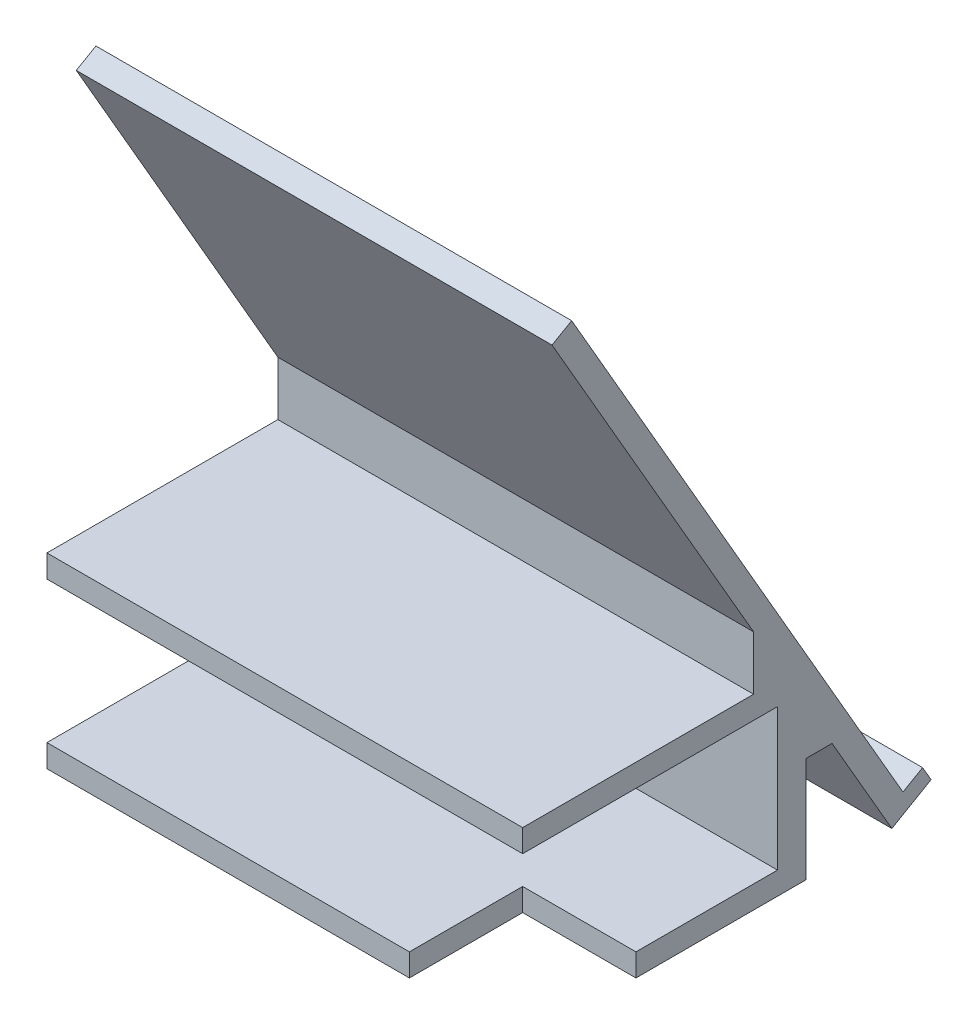
SolidWorks part; units mm, degrees
ref_plane "Спереди" through (0, 0, 0) normal (0, 0, 1) x (1, 0, 0)
ref_plane "Сверху" through (0, 0, 0) normal (0, 1, 0) x (1, 0, 0)
ref_plane "Справа" through (0, 0, 0) normal (1, 0, 0) x (0, 0, -1)
sketch "Эскиз1" plane through (0, 0, 0) normal (1, 0, 0) x (0, 0, -1)
  line L1 (0, 0) -> (50, 0)
  line L2 (0, 0) -> (0, 4)
  line L3 (0, 4) -> (50, 4)
  line L4 (50, 0) -> (50, 4)
  line L5 (50, 0) -> (45, 0)
  line L6 (50, 0) -> (50, 33)
  line L7 (50, 33) -> (45, 33)
  line L8 (45, 0) -> (45, 33)
  line L9 (50, 33) -> (0, 33)
  line L10 (50, 33) -> (50, 29)
  line L11 (50, 29) -> (0, 29)
  line L12 (0, 33) -> (0, 29)
  line L13 (5.1867, 104.1886) -> (8.6508, 106.1886)
  line L14 (8.6508, 106.1886) -> (68.6508, 2.2655)
  line L15 (68.6508, 2.2655) -> (65.1867, 0.2655)
  line L17 (5.1867, 104.1886) -> (65.1867, 0.2655)
  dimension "D1" = 4
  dimension "D2" = 4
  dimension "D3" = 50
  dimension "D4" = 50
  dimension "D5" = 5
  dimension "D6" = 60
  dimension "D7" = 4
  dimension "D8" = 120
  dimension "D9" = 25
extrude "Бобышка-Вытянуть1" add sketch "Эскиз1" along normal blind 84 contours L17 L11 L8 L3 L6 | L8 L1 L4 L3 | L13 L17 L7 L6 L15 L14 | L11 L17 L6
sketch "Эскиз2" plane through (0, 0, 0) normal (0, -1, 0) x (1, 0, 0)
  line L0 (64, 0) -> (64, -20)
  line L1 (84, 0) -> (0, 0) construction
  line L2 (64, -20) -> (84, -20)
  line L3 (84, 0) -> (84, -50) construction
  line L4 (64, 0) -> (84, 0)
  line L5 (84, 0) -> (84, -20)
  dimension "D1" = 20
  dimension "D2" = 20
extrude "Вырез-Вытянуть1" cut sketch "Эскиз2" against normal blind 14
sketch "Эскиз3" plane through (84, 0, 0) normal (1, 0, 0) x (0, 0, -1)
  line L0 (68.6508, 2.2655) -> (72.1149, 4.2655)
  line L1 (72.1149, 4.2655) -> (70.6149, 6.8636)
  line L2 (70.6149, 6.8636) -> (67.1508, 4.8636)
  line L3 (8.6508, 106.1886) -> (68.6508, 2.2655) construction
  line L4 (67.1508, 4.8636) -> (68.6508, 2.2655)
  line L5 (40.7782, 42.5423) -> (40.7782, 33)
  line L6 (5.1867, 104.1886) -> (46.2875, 33) construction
  line L7 (46.2875, 33) -> (0, 33) construction
  line L8 (40.7782, 33) -> (46.2875, 33)
  line L9 (46.2875, 33) -> (40.7782, 42.5423)
  line L10 (50, 26.5697) -> (50, 18.5528)
  line L11 (50, 0) -> (50, 26.5697) construction
  line L12 (50, 18.5528) -> (54.6286, 18.5528)
  line L13 (50, 26.5697) -> (65.1867, 0.2655) construction
  line L14 (54.6286, 18.5528) -> (50, 26.5697)
  dimension "D1" = 4
  dimension "D2" = 3
extrude "Бобышка-Вытянуть2" add sketch "Эскиз3" against normal up to surface (84 mm away) up to face at (0, 28.5752, -29.5356)
